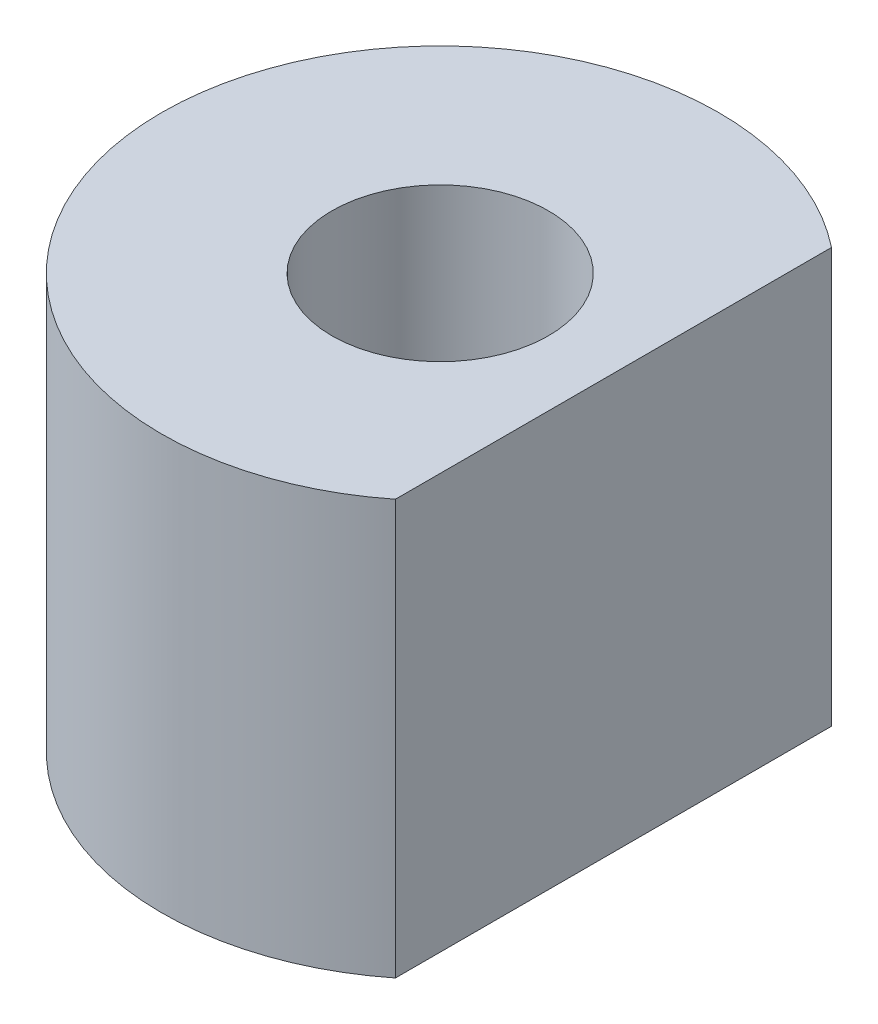
SolidWorks part; units mm, degrees
ref_plane "前视基准面" through (0, 0, 0) normal (0, 0, 1) x (1, 0, 0)
ref_plane "上视基准面" through (0, 0, 0) normal (0, 1, 0) x (1, 0, 0)
ref_plane "右视基准面" through (0, 0, 0) normal (1, 0, 0) x (0, 0, -1)
other "Configuration Table"
sketch "草图2" plane through (0, 0, 0) normal (0, 1, 0) x (1, 0, 0)
  line L0 (2.8, 3.5228) -> (2.8, -3.5228)
  circle A18 centre (0, 0) radius 4.5
  circle A19 centre (0, 0) radius 1.75
  dimension "D1" = 3.5
  dimension "D2" = 9
  dimension "D3" = 2.8
extrude "凸台-拉伸1" add sketch "草图2" along normal blind 6.7 contours L0 A18 A19
